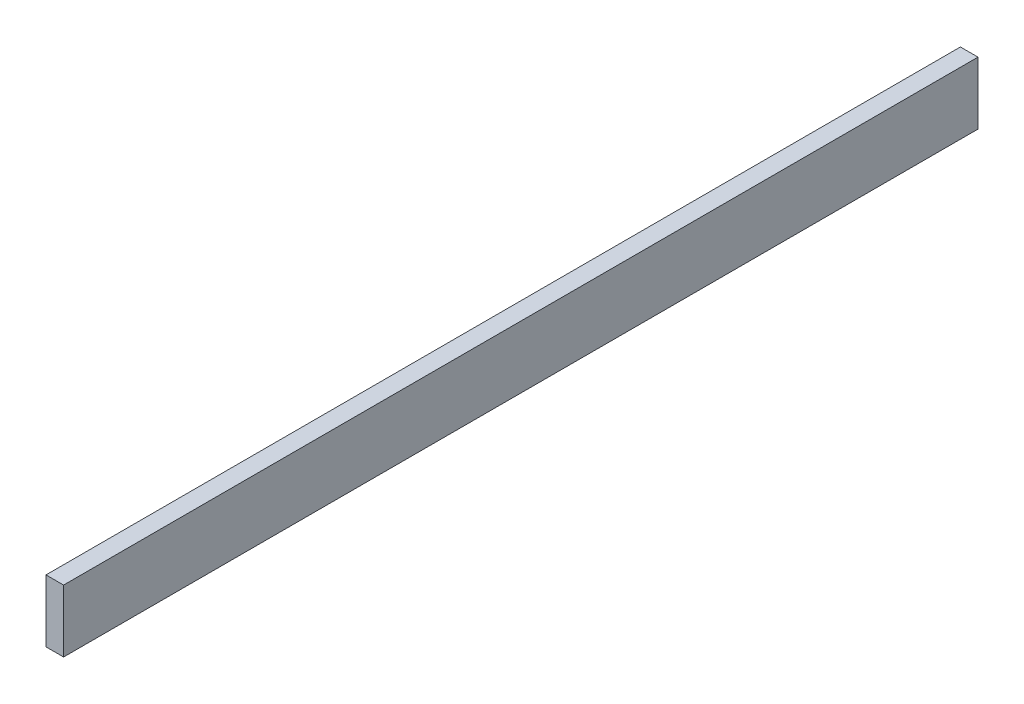
SolidWorks part; units mm, degrees
ref_plane "Front Plane" through (0, 0, 0) normal (0, 0, 1) x (1, 0, 0)
ref_plane "Top Plane" through (0, 0, 0) normal (0, 1, 0) x (1, 0, 0)
ref_plane "Right Plane" through (0, 0, 0) normal (1, 0, 0) x (0, 0, -1)
other "Configuration Table"
sketch "Sketch1" plane through (0, 0, 0) normal (0, 0, 1) x (1, 0, 0)
  line L1 (0, 14) -> (12.7, 14)
  line L2 (0, 14) -> (0, 59)
  line L3 (0, 59) -> (12.7, 59)
  line L4 (12.7, 14) -> (12.7, 59)
extrude "CEK_1L_ray_ic_profil_sol_1" add sketch "Sketch1" against normal blind 660 separate body
